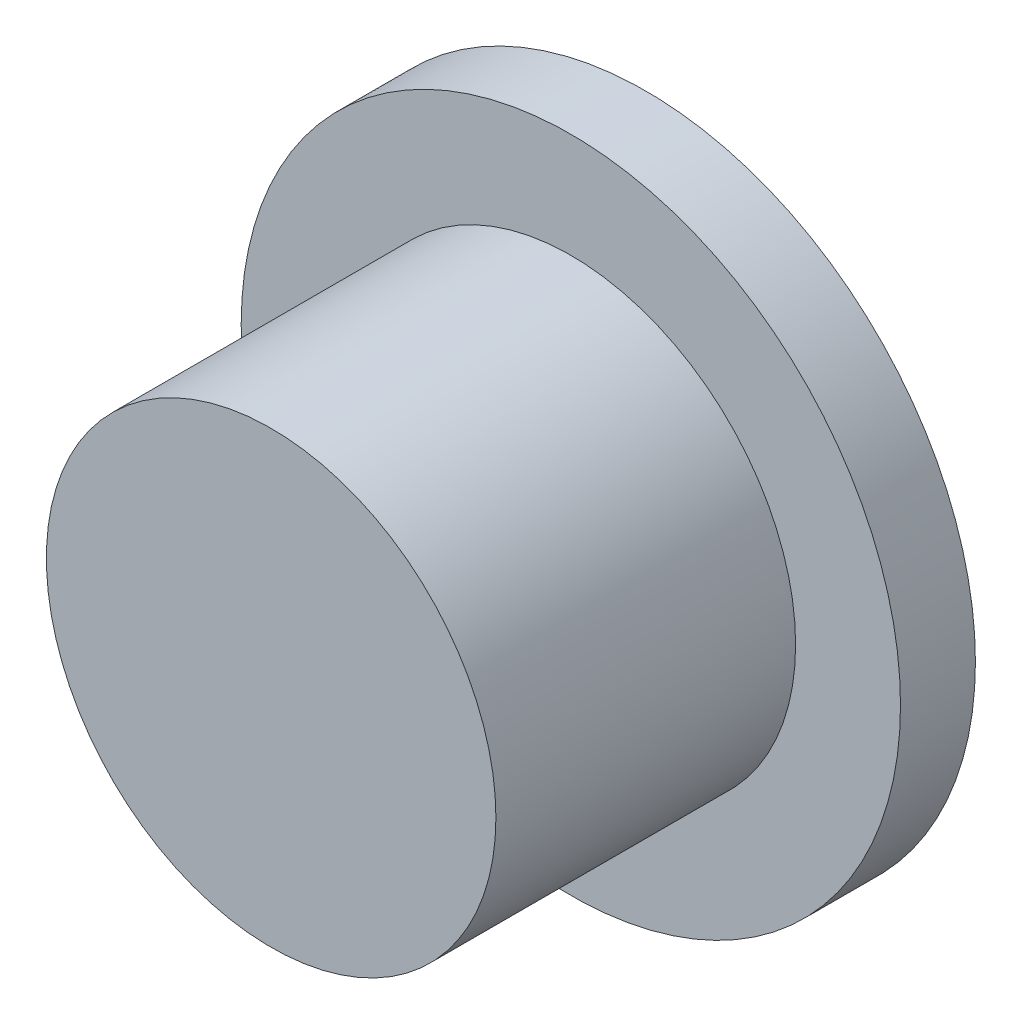
SolidWorks part; units mm, degrees
ref_plane "Plan de face" through (0, 0, 0) normal (0, 0, 1) x (1, 0, 0)
ref_plane "Plan de dessus" through (0, 0, 0) normal (0, 1, 0) x (1, 0, 0)
ref_plane "Plan de droite" through (0, 0, 0) normal (1, 0, 0) x (0, 0, -1)
sketch "Esquisse1" plane through (0, 0, 0) normal (0, 0, 1) x (1, 0, 0)
  circle A0 centre (0, 0) radius 15
extrude "Boss.-Extru.1" add sketch "Esquisse1" along normal blind 20
sketch "Esquisse2" plane through (0, 0, 0) normal (0, 0, -1) x (-1, 0, 0)
  circle A0 centre (0, 0) radius 22
extrude "Boss.-Extru.2" add sketch "Esquisse2" along normal blind 5
